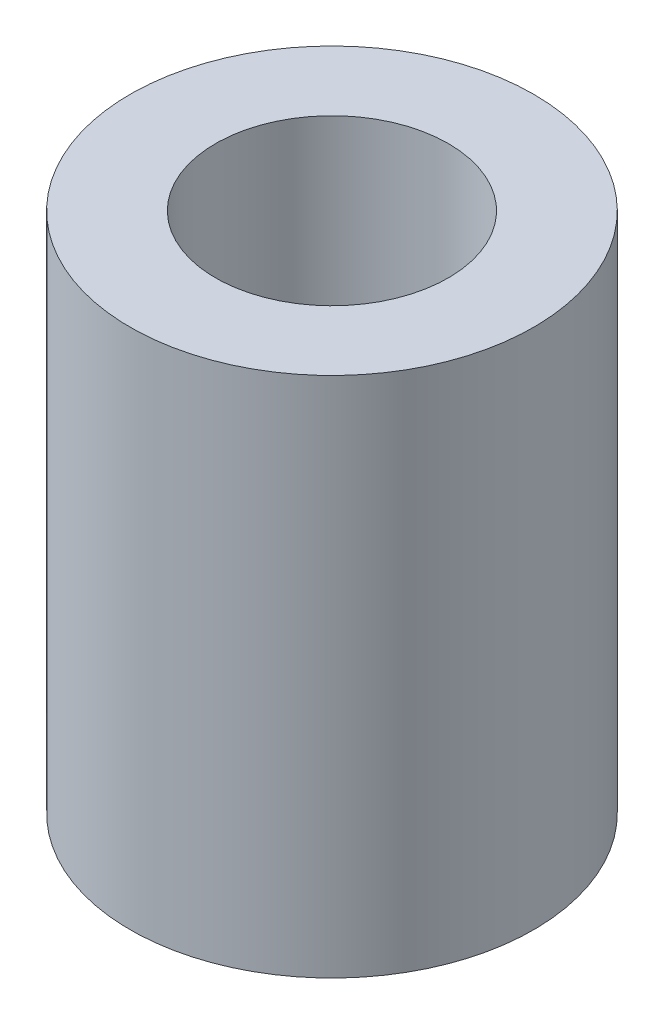
SolidWorks part; units mm, degrees
ref_plane "Front Plane" through (0, 0, 0) normal (0, 0, 1) x (1, 0, 0)
ref_plane "Top Plane" through (0, 0, 0) normal (0, 1, 0) x (1, 0, 0)
ref_plane "Right Plane" through (0, 0, 0) normal (1, 0, 0) x (0, 0, -1)
sketch "Sketch1" plane through (0, 0, 0) normal (0, 1, 0) x (1, 0, 0)
  circle A0 centre (0, 0) radius 16.51
  circle A1 centre (0, 0) radius 9.525
  dimension "D1" = 19.05
  dimension "D2" = 33.02
extrude "Boss-Extrude1" add sketch "Sketch1" along normal blind 42.7
